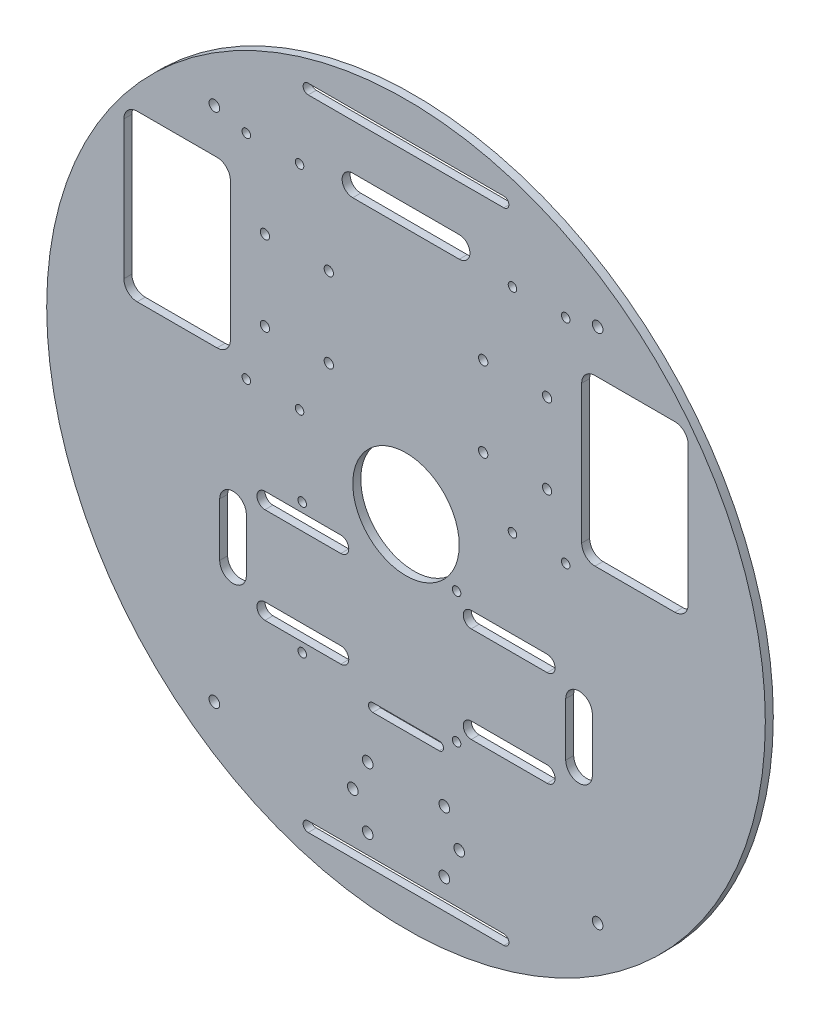
SolidWorks part; units mm, degrees
ref_plane "前视基准面" through (0, 0, 0) normal (0, 0, 1) x (1, 0, 0)
ref_plane "上视基准面" through (0, 0, 0) normal (0, 1, 0) x (1, 0, 0)
ref_plane "右视基准面" through (0, 0, 0) normal (1, 0, 0) x (0, 0, -1)
sketch "草图1" plane through (0, 0, 0) normal (0, 0, 1) x (1, 0, 0)
  line L0 (0, 135) -> (0, -135) construction
  line L1 (0, -99.3042) -> (86, 49.6521) construction
  line L2 (86, 49.6521) -> (-86, 49.6521) construction
  line L3 (-86, 49.6521) -> (0, -99.3042) construction
  line L4 (-106, 80.6521) -> (-66, 80.6521)
  line L5 (-106, 80.6521) -> (-106, 18.6521)
  line L6 (-106, 18.6521) -> (-66, 18.6521)
  line L7 (-66, 80.6521) -> (-66, 18.6521)
  line L8 (-106, 80.6521) -> (-66, 18.6521) construction
  line L9 (-106, 18.6521) -> (-66, 80.6521) construction
  line L10 (106, 80.6521) -> (66, 80.6521)
  line L11 (66, 80.6521) -> (66, 18.6521)
  line L12 (106, 80.6521) -> (66, 18.6521) construction
  line L13 (106, 18.6521) -> (66, 18.6521)
  line L14 (106, 18.6521) -> (66, 80.6521) construction
  line L15 (106, 80.6521) -> (106, 18.6521)
  line L17 (-14.4, -87.8042) -> (14.4, -87.8042) construction
  line L18 (-14.4, -87.8042) -> (-14.4, -110.8042) construction
  line L19 (-14.4, -110.8042) -> (14.4, -110.8042) construction
  line L20 (14.4, -87.8042) -> (14.4, -110.8042) construction
  line L21 (-14.4, -87.8042) -> (14.4, -110.8042) construction
  line L22 (-14.4, -110.8042) -> (14.4, -87.8042) construction
  line L29 (-53, 64.6521) -> (-29, 64.6521) construction
  line L30 (-53, 64.6521) -> (-53, 34.6521) construction
  line L31 (-53, 34.6521) -> (-29, 34.6521) construction
  line L32 (-29, 64.6521) -> (-29, 34.6521) construction
  line L33 (-53, 64.6521) -> (-29, 34.6521) construction
  line L34 (-53, 34.6521) -> (-29, 64.6521) construction
  circle A0 centre (0, 0) radius 135
  circle A1 centre (0, 0) radius 49.6521 construction
  circle A2 centre (-53, 64.6521) radius 1.75
  circle A3 centre (-29, 64.6521) radius 1.75
  circle A4 centre (-53, 34.6521) radius 1.75
  circle A5 centre (-29, 34.6521) radius 1.75
  circle A6 centre (53, 34.6521) radius 1.75
  circle A7 centre (29, 34.6521) radius 1.75
  circle A8 centre (29, 64.6521) radius 1.75
  circle A9 centre (53, 64.6521) radius 1.75
  circle A10 centre (20, -99.3042) radius 2
  circle A11 centre (14.4, -87.8042) radius 2
  circle A12 centre (14.4, -110.8042) radius 2
  circle A13 centre (-14.4, -87.8042) radius 2
  circle A14 centre (-14.4, -110.8042) radius 2
  circle A15 centre (-20, -99.3042) radius 2
  point P25 (0, 49.6521)
  point P26 (-41, 49.6521)
  point P30 (0, 49.6521)
  dimension "D1" = 270
  dimension "D9" = 3.5
  dimension "D10" = 3.5
  dimension "D11" = 3.5
  dimension "D12" = 3.5
  dimension "D14" = 20
  dimension "D2" = 40
  dimension "D3" = 62
  dimension "D4" = 41
  dimension "D5" = 25
  dimension "D6" = 28.8
  dimension "D7" = 24
  dimension "D8" = 30
  dimension "D13" = 23
extrude "凸台-拉伸1" add sketch "草图1" along normal blind 3
fillet "圆角1" radius 5 8 edges at (106, 80.6521, 1.5) (66, 80.6521, 1.5) (66, 18.6521, 1.5) (106, 18.6521, 1.5) (-66, 18.6521, 1.5) (-106, 18.6521, 1.5) (-106, 80.6521, 1.5) (-66, 80.6521, 1.5)
sketch "草图2" plane through (0, 0, 3) normal (0, 0, 1) x (1, 0, 0)
  line L1 (-72, 97) -> (72, 97) construction
  line L2 (-72, 97) -> (-72, -97) construction
  line L3 (-72, -97) -> (72, -97) construction
  line L4 (72, 97) -> (72, -97) construction
  line L5 (-72, 97) -> (72, -97) construction
  line L6 (-72, -97) -> (72, 97) construction
  line L7 (24.5056, -55) -> (53, -55)
  line L8 (-53, -19) -> (-24.5056, -19)
  line L9 (-53, -19) -> (-53, -61) construction
  line L10 (-53, -61) -> (-24.5056, -61)
  line L11 (53, -19) -> (53, -61) construction
  line L12 (-53, -19) -> (53, -61) construction
  line L13 (-53, -61) -> (53, -19) construction
  line L14 (-53, -25) -> (-24.5056, -25)
  line L15 (-53, -25) -> (-53, -55) construction
  line L16 (-53, -55) -> (-24.5056, -55)
  line L17 (53, -25) -> (53, -55) construction
  line L18 (-53, -25) -> (53, -55) construction
  line L19 (-53, -55) -> (53, -25) construction
  line L20 (24.5056, -25) -> (53, -25)
  line L21 (24.5056, -19) -> (53, -19)
  line L22 (24.5056, -61) -> (53, -61)
  line L23 (40, 94) -> (40, 14) construction
  line L24 (-65, -30) -> (65, -30) construction
  line L25 (-65, -30) -> (-65, -50) construction
  line L26 (-65, -50) -> (65, -50) construction
  line L27 (65, -30) -> (65, -50) construction
  line L28 (-65, -30) -> (65, -50) construction
  line L29 (-65, -50) -> (65, -30) construction
  line L30 (-70, -30) -> (-60, -30) construction
  line L31 (-70, -30) -> (-70, -50)
  line L32 (-70, -50) -> (-60, -50) construction
  line L33 (-60, -30) -> (-60, -50)
  line L34 (-70, -30) -> (-60, -50) construction
  line L35 (-70, -50) -> (-60, -30) construction
  line L36 (60, -30) -> (70, -30) construction
  line L37 (60, -30) -> (60, -50)
  line L38 (60, -50) -> (70, -50) construction
  line L39 (70, -30) -> (70, -50)
  line L40 (60, -30) -> (70, -50) construction
  line L41 (60, -50) -> (70, -30) construction
  line L43 (35, -12.5) -> (-35, -12.5) construction
  line L44 (35, -12.5) -> (35, -67.5) construction
  line L45 (-42.5, -12) -> (42.5, -12) construction
  line L46 (-42.5, -12) -> (-42.5, -68) construction
  line L47 (-42.5, -68) -> (42.5, -68) construction
  line L48 (-135, 0) -> (135, 0) construction
  line L49 (-36.7556, -118.1) -> (36.7556, -121.9) construction
  line L50 (-36.7556, 121.9) -> (36.7556, 121.9)
  line L51 (-36.7556, 121.9) -> (-36.7556, 118.1) construction
  line L52 (-36.7556, 118.1) -> (36.7556, 118.1)
  line L53 (36.7556, 121.9) -> (36.7556, 118.1) construction
  line L54 (-36.7556, 121.9) -> (36.7556, 118.1) construction
  line L55 (-36.7556, 118.1) -> (36.7556, 121.9) construction
  line L56 (-36.7556, -121.9) -> (36.7556, -118.1) construction
  line L57 (36.7556, -121.9) -> (36.7556, -118.1) construction
  line L58 (-36.7556, -121.9) -> (-36.7556, -118.1) construction
  line L59 (-36.7556, -118.1) -> (36.7556, -118.1)
  line L60 (-36.7556, -121.9) -> (36.7556, -121.9)
  line L61 (-40, 94) -> (-40, 14) construction
  line L62 (-60, 94) -> (60, 94) construction
  line L63 (-60, 94) -> (-60, 14) construction
  line L64 (-60, 14) -> (60, 14) construction
  line L65 (60, 94) -> (60, 14) construction
  line L66 (-60, 94) -> (60, 14) construction
  line L67 (-60, 14) -> (60, 94) construction
  line L68 (42.5, -12) -> (42.5, -68) construction
  line L69 (-42.5, -12) -> (42.5, -68) construction
  line L70 (-42.5, -68) -> (42.5, -12) construction
  line L71 (-39, -15.5) -> (19, -15.5) construction
  line L72 (-39, -15.5) -> (-39, -64.5) construction
  line L73 (-39, -64.5) -> (19, -64.5) construction
  line L74 (19, -15.5) -> (19, -64.5) construction
  line L75 (-39, -15.5) -> (19, -64.5) construction
  line L76 (-39, -64.5) -> (19, -15.5) construction
  line L77 (35, -67.5) -> (-35, -67.5) construction
  line L78 (-35, -12.5) -> (-35, -67.5) construction
  line L79 (35, -12.5) -> (-35, -67.5) construction
  line L80 (35, -67.5) -> (-35, -12.5) construction
  line L81 (12.5, -70.7) -> (-12.5, -70.7)
  line L82 (12.5, -70.7) -> (12.5, -67.5) construction
  line L83 (12.5, -67.5) -> (-12.5, -67.5)
  line L84 (-12.5, -70.7) -> (-12.5, -67.5) construction
  line L85 (12.5, -70.7) -> (-12.5, -67.5) construction
  line L86 (12.5, -67.5) -> (-12.5, -70.7) construction
  line L87 (20, 101) -> (-20, 101)
  line L88 (20, 101) -> (20, 93) construction
  line L89 (20, 93) -> (-20, 93)
  line L90 (-20, 101) -> (-20, 93) construction
  line L91 (20, 101) -> (-20, 93) construction
  line L92 (20, 93) -> (-20, 101) construction
  circle A0 centre (0, 0) radius 20
  circle A1 centre (-72, 97) radius 2
  circle A2 centre (72, 97) radius 2
  circle A3 centre (72, -97) radius 2
  circle A4 centre (-72, -97) radius 2
  arc A5 (-53, -19) -> (-53, -25) centre (-53, -22) ccw
  arc A6 (-53, -55) -> (-53, -61) centre (-53, -58) ccw
  arc A7 (-24.5056, -19) -> (-24.5056, -25) centre (-24.5056, -22) cw
  arc A8 (-24.5056, -61) -> (-24.5056, -55) centre (-24.5056, -58) ccw
  arc A9 (53, -55) -> (53, -61) centre (53, -58) cw
  arc A10 (53, -19) -> (53, -25) centre (53, -22) cw
  arc A11 (24.5056, -61) -> (24.5056, -55) centre (24.5056, -58) cw
  arc A12 (24.5056, -19) -> (24.5056, -25) centre (24.5056, -22) ccw
  arc A13 (-70, -30) -> (-60, -30) centre (-65, -30) cw
  arc A14 (-70, -50) -> (-60, -50) centre (-65, -50) ccw
  arc A15 (60, -30) -> (70, -30) centre (65, -30) cw
  arc A16 (60, -50) -> (70, -50) centre (65, -50) ccw
  circle A17 centre (-60, 94) radius 1.6
  circle A18 centre (-60, 14) radius 1.6
  circle A19 centre (-40, 94) radius 1.6
  circle A20 centre (-40, 14) radius 1.6
  circle A21 centre (60, 14) radius 1.6
  circle A22 centre (60, 94) radius 1.6
  circle A23 centre (40, 94) radius 1.6
  circle A24 centre (40, 14) radius 1.6
  circle A25 centre (0, 0) radius 135 construction
  arc A26 (36.7556, 121.9) -> (36.7556, 118.1) centre (36.7556, 120) cw
  arc A27 (-36.7556, 121.9) -> (-36.7556, 118.1) centre (-36.7556, 120) ccw
  arc A28 (-36.7556, -121.9) -> (-36.7556, -118.1) centre (-36.7556, -120) cw
  arc A29 (36.7556, -121.9) -> (36.7556, -118.1) centre (36.7556, -120) ccw
  circle A30 centre (-39, -15.5) radius 1.6
  circle A31 centre (19, -15.5) radius 1.6
  circle A32 centre (-39, -64.5) radius 1.6
  circle A33 centre (19, -64.5) radius 1.6
  arc A34 (-12.5, -67.5) -> (-12.5, -70.7) centre (-12.5, -69.1) ccw
  arc A35 (12.5, -67.5) -> (12.5, -70.7) centre (12.5, -69.1) cw
  arc A36 (20, 101) -> (20, 93) centre (20, 97) cw
  arc A37 (-20, 101) -> (-20, 93) centre (-20, 97) ccw
  point P25 (0, 54)
  point P32 (0, -40)
  point P37 (-65, -40)
  point P38 (0, -40)
  point P39 (0, -40)
  point P52 (65, -40)
  point P61 (0, -40)
  point P77 (-10, -40)
  point P83 (0, 120)
  point P96 (0, -120)
  point P97 (0, -40)
  point P106 (-42.5, -40)
  point P111 (0, -40)
  point P116 (0, -69.1)
  dimension "D1" = 144
  dimension "D13" = 3.8
  dimension "D15" = 4
  dimension "D16" = 4
  dimension "D17" = 4
  dimension "D18" = 4
  dimension "D12" = 56
  dimension "D26" = 6
  dimension "D27" = 3
  dimension "D28" = 3
  dimension "D2" = 194
  dimension "D3" = 30
  dimension "D4" = 20
  dimension "D5" = 106
  dimension "D6" = 130
  dimension "D7" = 40
  dimension "D8" = 10
  dimension "D9" = 10
  dimension "D10" = 54
  dimension "D14" = 120
  dimension "D19" = 80
  dimension "D20" = 120
  dimension "D21" = 85
  dimension "D22" = 3.5
  dimension "D23" = 58
  dimension "D24" = 49
  dimension "D25" = 3.5
  dimension "D29" = 70
  dimension "D30" = 55
  dimension "D31" = 25
  dimension "D32" = 3.2
  dimension "D33" = 8
  dimension "D34" = 40
extrude "切除-拉伸1" cut sketch "草图2" against normal blind 10
sketch "草图3" plane through (0, 0, 3) normal (0, 0, 1) x (1, 0, 0)
  line L0 (0, 0) -> (0, -135) construction
  line L1 (0, 93) -> (0, 0) construction
  line L2 (35, -8.8786) -> (-35, -8.8786) construction
  line L3 (35, -8.8786) -> (35, -63.8786) construction
  line L4 (35, -63.8786) -> (-35, -63.8786) construction
  line L5 (-35, -8.8786) -> (-35, -63.8786) construction
  line L6 (35, -8.8786) -> (-35, -63.8786) construction
  line L7 (35, -63.8786) -> (-35, -8.8786) construction
  line L8 (-20, 93) -> (20, 93) construction
  circle A0 centre (0, 0) radius 135 construction
  point P6 (0, -36.3786)
  dimension "D1" = 55
  dimension "D2" = 70
  dimension "D3" = 93
sketch "草图4" plane through (0, 0, 0) normal (0, 0, -1) x (-1, 0, 0)
  line L1 (-88.3346, 51) -> (0, -102)
  line L2 (0, -102) -> (88.3346, 51)
  line L3 (88.3346, 51) -> (-88.3346, 51)
  circle A0 centre (0, 0) radius 102 construction
  point P1 (0, 51)
  dimension "D3" = 204
  dimension "D1" = 176.6692
  dimension "D2" = 153
